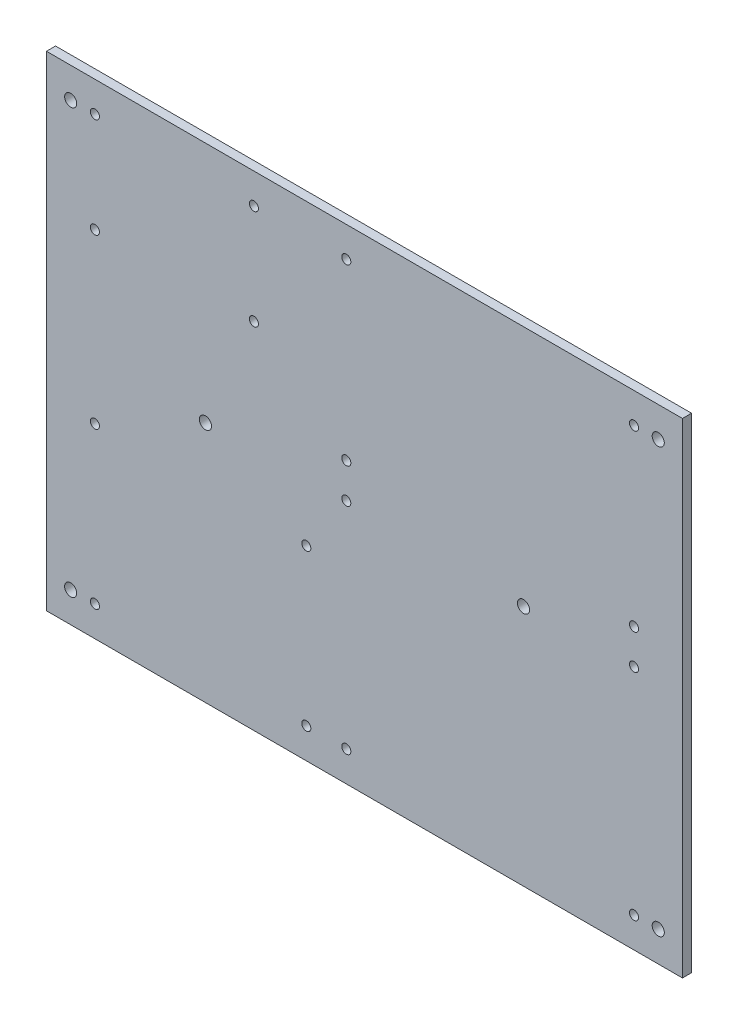
SolidWorks part; units mm, degrees
other "Markup1"
sketch "Sketch6" plane through (-105, -80, 3) normal (0, 0, 1) x (1, 0, 0)
ref_plane "Front Plane" through (0, 0, 0) normal (0, 0, 1) x (1, 0, 0)
ref_plane "Top Plane" through (0, 0, 0) normal (0, 1, 0) x (1, 0, 0)
ref_plane "Right Plane" through (0, 0, 0) normal (1, 0, 0) x (0, 0, -1)
sketch "Sketch1" plane through (0, 0, 0) normal (0, 0, 1) x (1, 0, 0)
  line L0 (55, 0) -> (-55, 0) construction
  line L1 (-105, 80) -> (105, 80)
  line L2 (-105, 80) -> (-105, -80)
  line L3 (-105, -80) -> (105, -80)
  line L4 (105, 80) -> (105, -80)
  line L5 (0, -55) -> (0, 55) construction
  circle A0 centre (-97, 70) radius 2
  circle A2 centre (-97, -70) radius 2
  circle A3 centre (97, -70) radius 2
  circle A4 centre (97, 70) radius 2
  circle A5 centre (-52.5, 0) radius 2
  circle A7 centre (52.5, 0) radius 2
  dimension "D5" = 4
  dimension "D6" = 10
  dimension "D7" = 6
  dimension "D8" = 4
  dimension "D9" = 80
  dimension "D10" = 52.5
  dimension "D1" = 210
  dimension "D2" = 160
  dimension "D3" = 80
  dimension "D4" = 105
extrude "Boss-Extrude1" add sketch "Sketch1" along normal blind 3 contours L4 L1 L2 L3 A2 A0 A3 A4
sketch "Sketch2" plane through (0, 0, 3) normal (0, 0, 1) x (1, 0, 0)
  line L1 (-105, 80) -> (105, 80) construction
  line L2 (105, 80) -> (105, -80) construction
  circle A0 centre (-6, 70) radius 1.5
  circle A1 centre (89, 70) radius 1.5
  circle A2 centre (-6, 12.5) radius 1.5
  circle A3 centre (89, 12.5) radius 1.5
  dimension "D1" = 3
  dimension "D2" = 3
  dimension "D3" = 3
  dimension "D4" = 3
  dimension "D5" = 95
  dimension "D6" = 57.5
  dimension "D7" = 16
  dimension "D8" = 10
extrude "LVPCB Hole" cut sketch "Sketch2" against normal blind 20
sketch "Sketch4" plane through (0, 0, 3) normal (0, 0, 1) x (1, 0, 0)
  line L0 (-105, -80) -> (105, -80) construction
  line L1 (105, 80) -> (105, -80) construction
  circle A0 centre (-6, 1) radius 1.5
  circle A1 centre (89, 1) radius 1.5
  circle A2 centre (-6, -70) radius 1.5
  circle A3 centre (89, -70) radius 1.5
  dimension "D1" = 95
  dimension "D2" = 71
  dimension "D3" = 3
  dimension "D4" = 3
  dimension "D5" = 3
  dimension "D6" = 3
  dimension "D7" = 10
  dimension "D8" = 16
extrude "SDC Hole" cut sketch "Sketch4" against normal blind 10
sketch "Sketch3" plane through (0, 0, 3) normal (0, 0, 1) x (1, 0, 0)
  line L0 (-105, 80) -> (-105, -80) construction
  line L1 (-105, -80) -> (105, -80) construction
  circle A0 centre (-89, -18.5) radius 1.5
  circle A1 centre (-19.2, -18.5) radius 1.5
  circle A2 centre (-89, -70) radius 1.5
  circle A3 centre (-19.2, -70) radius 1.5
  dimension "D1" = 69.8
  dimension "D2" = 51.5
  dimension "D3" = 3
  dimension "D4" = 3
  dimension "D5" = 3
  dimension "D6" = 3
  dimension "D7" = 16
  dimension "D8" = 10
extrude "TSAL LV Hole" cut sketch "Sketch3" against normal blind 10 contours A0 | A1 | A3 | A2
sketch "Sketch5" plane through (0, 0, 3) normal (0, 0, 1) x (1, 0, 0)
  line L2 (-105, 80) -> (-105, -80) construction
  line L3 (-105, 80) -> (105, 80) construction
  circle A0 centre (-89, 70) radius 1.5
  circle A1 centre (-36.5, 70) radius 1.5
  circle A2 centre (-89, 37) radius 1.5
  circle A3 centre (-36.5, 37) radius 1.5
  dimension "D1" = 52.5
  dimension "D2" = 33
  dimension "D3" = 16
  dimension "D4" = 10
  dimension "D5" = 3
  dimension "D6" = 3
  dimension "D7" = 3
  dimension "D8" = 3
extrude "BSPD Hole" cut sketch "Sketch5" against normal blind 10
